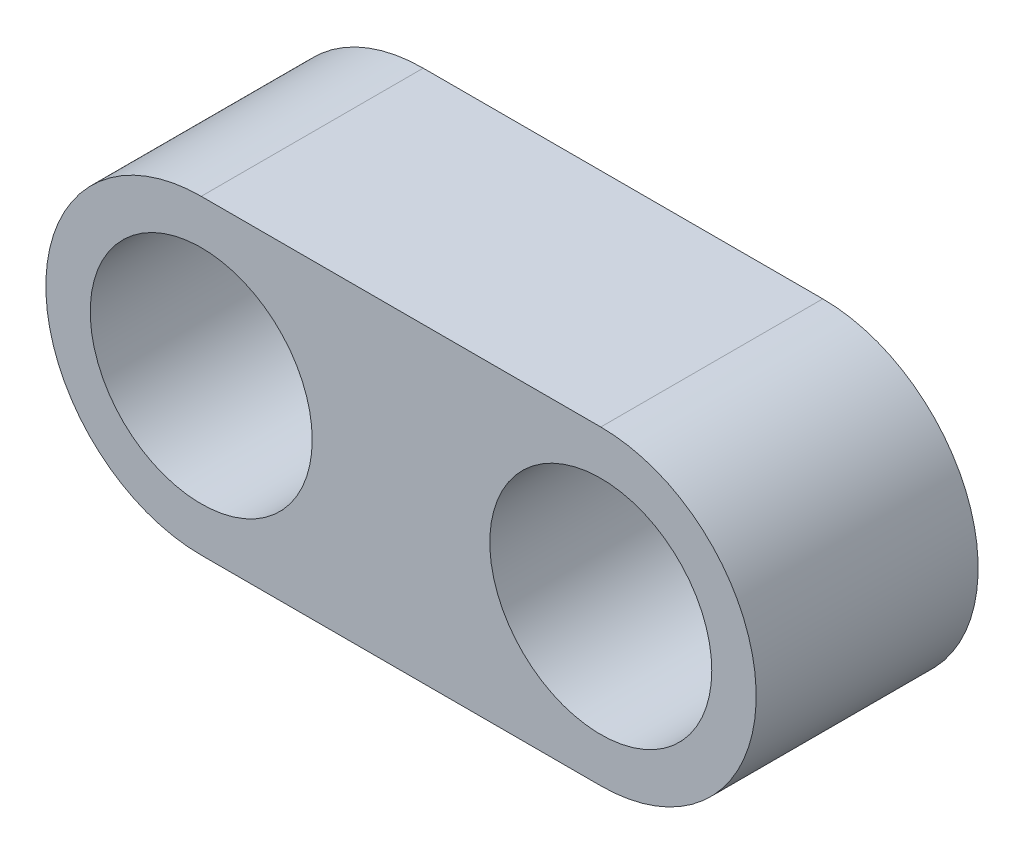
SolidWorks part; units mm, degrees
ref_plane "Front Plane" through (0, 0, 0) normal (0, 0, 1) x (1, 0, 0)
ref_plane "Top Plane" through (0, 0, 0) normal (0, 1, 0) x (1, 0, 0)
ref_plane "Right Plane" through (0, 0, 0) normal (1, 0, 0) x (0, 0, -1)
sketch "Sketch2" plane through (0, 0, 0) normal (0, 0, 1) x (1, 0, 0)
  line L0 (-9, 0) -> (9, 0) construction
  line L1 (-9, 0) -> (9, 0) construction
  line L2 (-9, 7) -> (9, 7)
  line L3 (-9, -7) -> (9, -7)
  circle A0 centre (-9, 0) radius 5
  circle A1 centre (9, 0) radius 5
  arc A2 (-9, 7) -> (-9, -7) centre (-9, 0) ccw
  arc A3 (9, -7) -> (9, 7) centre (9, 0) ccw
  point P5 (0, 0)
  dimension "D1" = 10
  dimension "D3" = 2
  dimension "D2" = 18
extrude "Boss-Extrude1" add sketch "Sketch2" along normal blind 10
